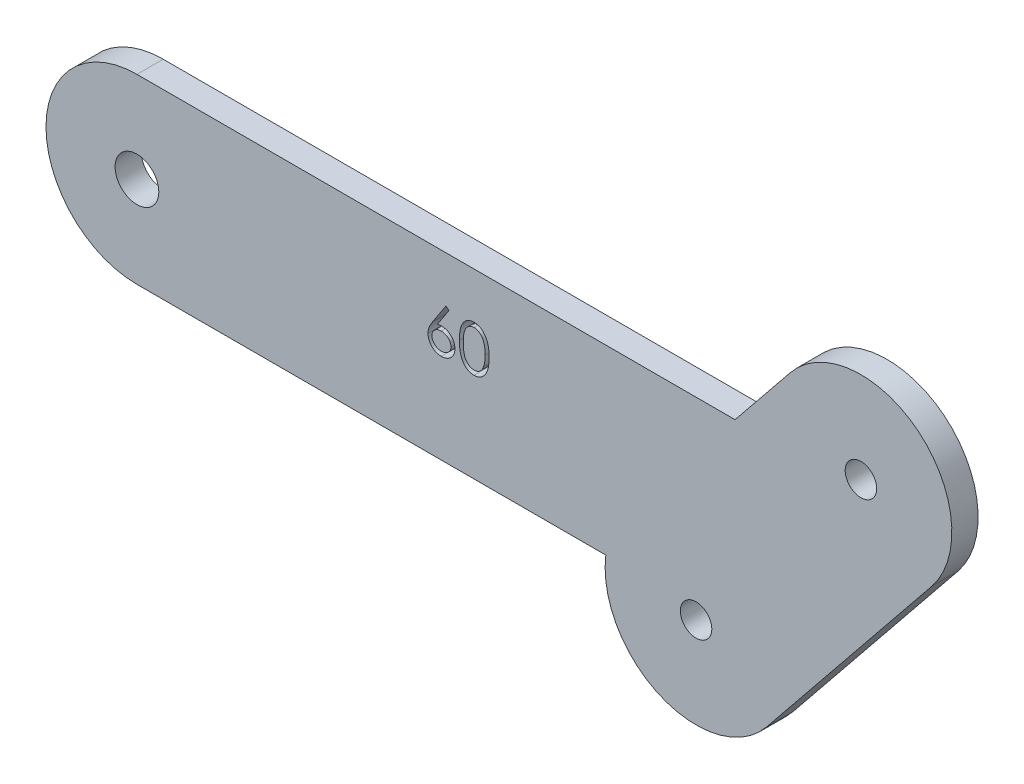
SolidWorks part; units mm, degrees
ref_plane "Front Plane" through (0, 0, 0) normal (0, 0, 1) x (1, 0, 0)
ref_plane "Top Plane" through (0, 0, 0) normal (0, 1, 0) x (1, 0, 0)
ref_plane "Right Plane" through (0, 0, 0) normal (1, 0, 0) x (0, 0, -1)
other "Configuration Table"
sketch "Sketch1" plane through (0, 0, 0) normal (0, 0, 1) x (1, 0, 0)
  line L0 (0, 0) -> (73.371, 0) construction
  line L1 (82.7986, 11.6671) -> (63.9434, -11.6671) construction
  line L2 (72.0325, -18.2035) -> (90.8877, 5.1306)
  line L3 (55.8542, -5.1306) -> (74.7094, 18.2035)
  line L4 (0, -10.4) -> (53.6208, -10.4)
  line L5 (0, 10.4) -> (68.4037, 10.4)
  arc A0 (72.0325, -18.2035) -> (55.8542, -5.1306) centre (63.9434, -11.6671) cw
  arc A1 (90.8877, 5.1306) -> (74.7094, 18.2035) centre (82.7986, 11.6671) ccw
  arc A2 (0, -10.4) -> (0, 10.4) centre (0, 0) cw
  circle A3 centre (0, 0) radius 2.5
  point P6 (73.371, 0)
  point P13 (60, 0)
  dimension "D3" = 10.4
  dimension "D5" = 10.4
  dimension "D6" = 10.4
  dimension "D7" = 5
  dimension "D1" = 51.06
  dimension "D2" = 30
  dimension "D4" = 60
extrude "Boss-Extrude1" add sketch "Sketch1" along normal blind 3 contours A2 L4 A0 L3 L5 | L2 A1 L3 A0
hole_wizard "M3 Clearance Hole1" positions "Sketch4" profile "Sketch3" hole size "M3" standard "ANSI Metric" end condition through all
sketch "Sketch4" plane through (0, 0, 3) normal (0, 0, 1) x (1, 0, 0)
  point P0 (63.9434, -11.6671)
  point P3 (82.7986, 11.6671)
sketch "Sketch3" plane through (63.9434, -11.6671, 3) normal (1, 0, 0) x (0, -1, 0)
  line L0 (0, 0) -> (0, 3)
  line L1 (0, 3) -> (1.8, 3)
  line L2 (1.8, 3) -> (1.8, 0)
  line L5 (1.8, 0) -> (0, 0)
  line L11 (0, -6.35) -> (0, 107.95) construction
  dimension "Thru Hole Dia." = 3.6
  dimension "Thru Hole Depth" = 3
sketch "Sketch5" plane through (0, 0, 3) normal (0, 0, 1) x (1, 0, 0)
  line L0 (0, 0) -> (73.371, 0) construction
  line L1 (0, 0) -> (73.371, 0) construction
  text T0 "60" font "Century Gothic" height 5
extrude "Cut-Extrude1" cut sketch "Sketch5" against normal blind 2
equation "\"D5@Sketch1\"=\"D3@Sketch1\""
equation "\"D6@Sketch1\"=\"D3@Sketch1\""
equation "\"length\"= 60"
equation "\"D4@Sketch1\"=\"length\""
